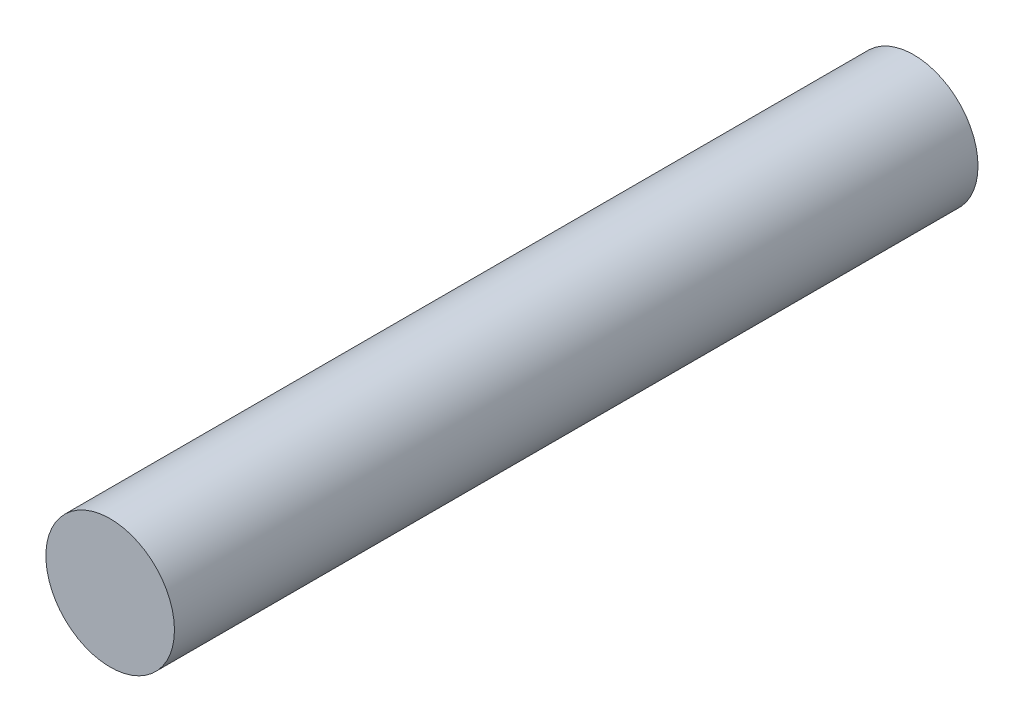
SolidWorks part; units mm, degrees
ref_plane "Alzado" through (0, 0, 0) normal (0, 0, 1) x (1, 0, 0)
ref_plane "Planta" through (0, 0, 0) normal (0, 1, 0) x (1, 0, 0)
ref_plane "Vista lateral" through (0, 0, 0) normal (1, 0, 0) x (0, 0, -1)
sketch "Sketch1" plane through (0, 0, 0) normal (0, 0, 1) x (1, 0, 0)
  circle A0 centre (0, 0) radius 8
  dimension "D1" = 16
extrude "Boss-Extrude1" add sketch "Sketch1" along normal mid plane 100
